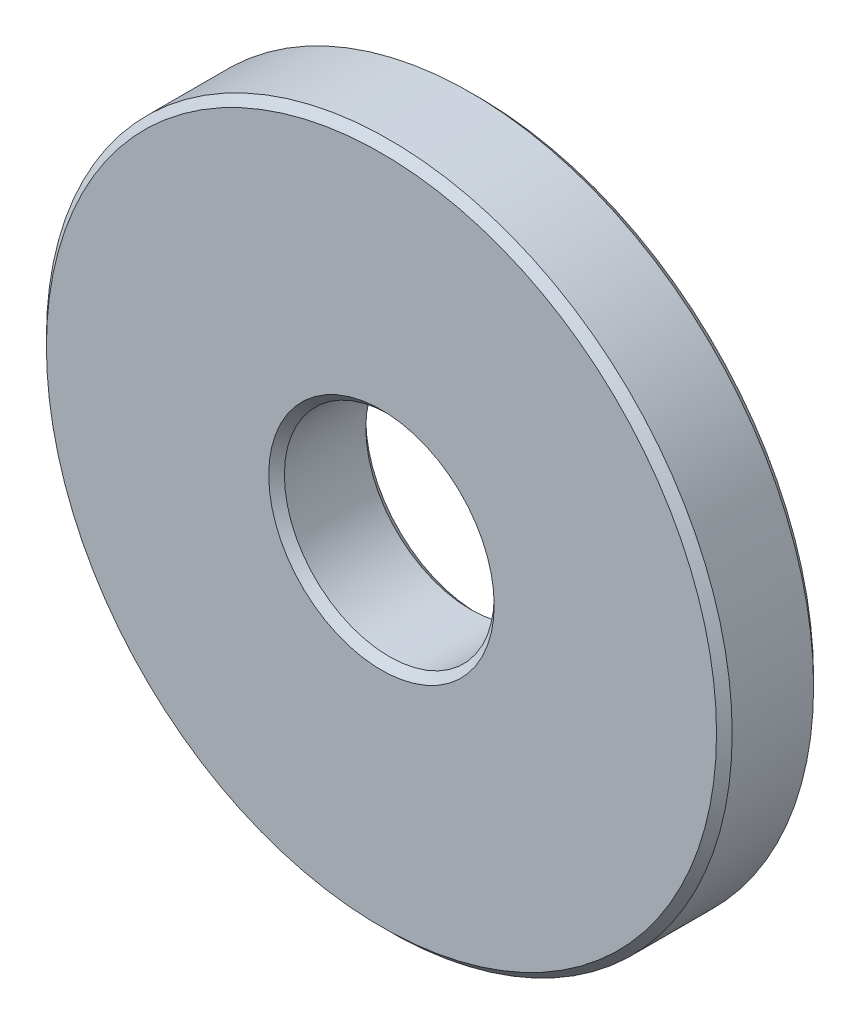
SolidWorks part; units mm, degrees
ref_plane "Front Plane" through (0, 0, 0) normal (0, 0, 1) x (1, 0, 0)
ref_plane "Top Plane" through (0, 0, 0) normal (0, 1, 0) x (1, 0, 0)
ref_plane "Right Plane" through (0, 0, 0) normal (1, 0, 0) x (0, 0, -1)
sketch "Sketch1" plane through (0, 0, 0) normal (0, 0, 1) x (1, 0, 0)
  circle A0 centre (0, 0) radius 10.95
  circle A1 centre (0, 0) radius 3.35
  dimension "D1" = 21.9
  dimension "D2" = 6.7
extrude "Boss-Extrude1" add sketch "Sketch1" along normal blind 3.1
chamfer "Chamfer1" distance 0.25 angle 45 4 edges at (3.35, 0, 3.1) (10.95, 0, 3.1) (3.35, 0, 0) (10.95, 0, 0)
